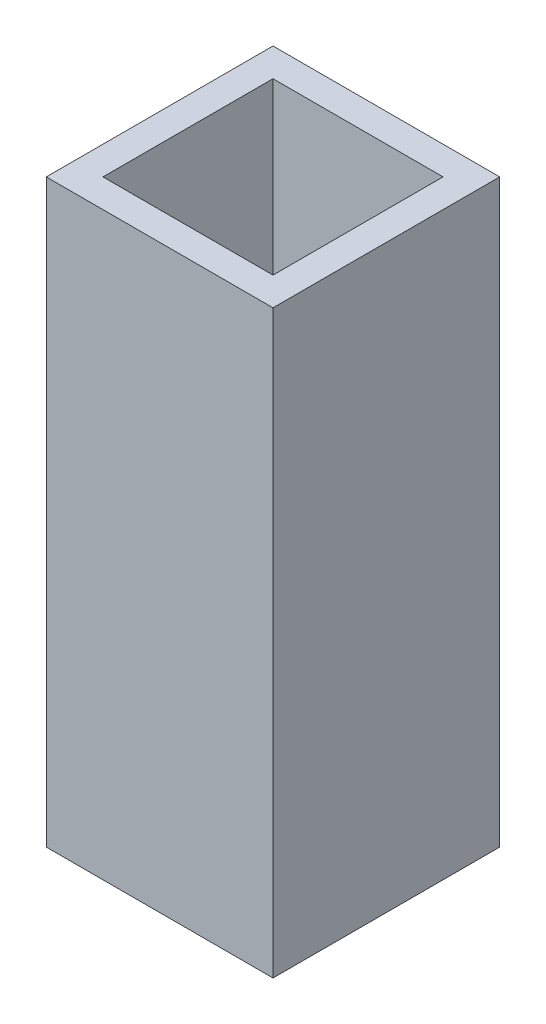
SolidWorks part; units mm, degrees
ref_plane "Front Plane" through (0, 0, 0) normal (0, 0, 1) x (1, 0, 0)
ref_plane "Top Plane" through (0, 0, 0) normal (0, 1, 0) x (1, 0, 0)
ref_plane "Right Plane" through (0, 0, 0) normal (1, 0, 0) x (0, 0, -1)
sketch "Sketch1" plane through (0, 0, 0) normal (0, 1, 0) x (1, 0, 0)
  line L1 (0, 0) -> (25.4, 0)
  line L2 (0, 0) -> (0, 25.4)
  line L3 (0, 25.4) -> (25.4, 25.4)
  line L4 (25.4, 0) -> (25.4, 25.4)
  dimension "D1" = 25.4
  dimension "D2" = 25.4
extrude "Boss-Extrude1" add sketch "Sketch1" along normal blind 65.024
sketch "Sketch4" plane through (0, 0, 0) normal (0, -1, 0) x (-1, 0, 0)
  line L0 (-25.4, 25.4) -> (0, 25.4) construction
  line L1 (-22.225, 3.175) -> (-3.175, 3.175)
  line L2 (-22.225, 3.175) -> (-22.225, 22.225)
  line L3 (-22.225, 22.225) -> (-3.175, 22.225)
  line L4 (-3.175, 3.175) -> (-3.175, 22.225)
  line L5 (0, 25.4) -> (0, 0) construction
  line L6 (0, 0) -> (-25.4, 0) construction
  line L7 (-25.4, 0) -> (-25.4, 25.4) construction
  dimension "D1" = 3.175
  dimension "D2" = 3.175
  dimension "D3" = 3.175
  dimension "D4" = 3.175
extrude "Cut-Extrude2" cut sketch "Sketch4" against normal through all
